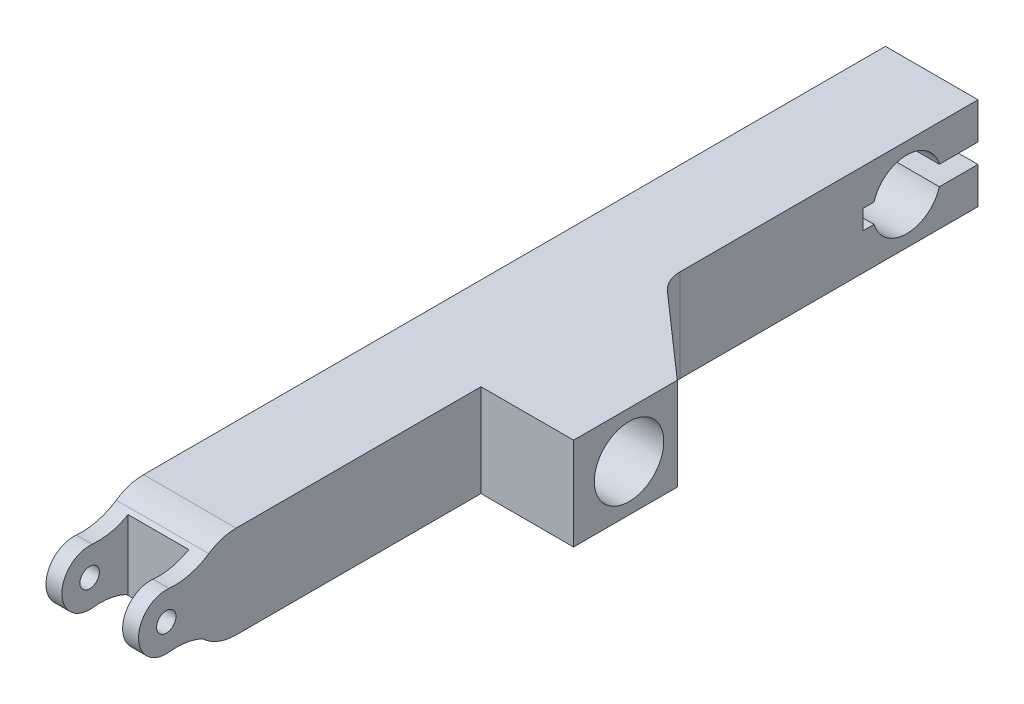
SolidWorks part; units mm, degrees
material "6061-T6 (SS)"
ref_plane "Front Plane" through (0, 0, 0) normal (0, 0, 1) x (1, 0, 0)
ref_plane "Top Plane" through (0, 0, 0) normal (0, 1, 0) x (1, 0, 0)
ref_plane "Right Plane" through (0, 0, 0) normal (1, 0, 0) x (0, 0, -1)
sketch "Sketch1" plane through (0, 0, 0) normal (1, 0, 0) x (0, 0, -1)
  line L0 (0, 0) -> (29.3372, 0) construction
  line L1 (29.3372, -19.05) -> (-175.2557, -19.05)
  line L2 (29.3372, -19.05) -> (29.3372, -4)
  line L3 (29.3372, 19.05) -> (-175.2557, 19.05)
  line L4 (-175.2557, -19.05) -> (-175.2557, 19.05)
  line L5 (-18.025, 0) -> (0, 0) construction
  line L6 (-18.025, 4) -> (-13.4425, 4)
  line L7 (-18.025, 4) -> (-18.025, -4)
  line L8 (-18.025, -4) -> (-13.4425, -4)
  line L10 (29.3372, 4) -> (29.3372, 19.05)
  line L11 (13.4425, 4) -> (29.3372, 4)
  line L12 (13.4425, -4) -> (29.3372, -4)
  line L13 (0, 0) -> (-152.4, 0) construction
  arc A0 (13.4425, 4) -> (-13.4425, 4) centre (0, 0) ccw
  arc A1 (-13.4425, -4) -> (13.4425, -4) centre (0, 0) ccw
  circle A2 centre (-152.4, 0) radius 14.2875
  point P13 (-14.025, 0)
  dimension "D1" = 28.05
  dimension "D6" = 28.575
  dimension "D2" = 8
  dimension "D3" = 4
  dimension "D4" = 38.1
  dimension "D5" = 152.4
extrude "Boss-Extrude1" add sketch "Sketch1" along normal blind 38.1
sketch "Sketch2" plane through (38.1, 0, 0) normal (1, 0, 0) x (0, 0, -1)
  line L0 (-175.2557, -19.05) -> (29.3372, -19.05) construction
  line L1 (-175.2557, 19.05) -> (-99.0557, 19.05)
  line L2 (-175.2557, 19.05) -> (-175.2557, -19.05)
  line L3 (-175.2557, -19.05) -> (-99.0557, -19.05)
  line L4 (-99.0557, 19.05) -> (-99.0557, -19.05)
  circle A0 centre (-152.4, 0) radius 14.2875 construction
  circle A1 centre (-152.4, 0) radius 14.2875
  dimension "D1" = 76.2
extrude "Boss-Extrude2" add sketch "Sketch2" along normal blind 38.1
sketch "Sketch3" plane through (0, 19.05, 0) normal (0, 1, 0) x (1, 0, 0)
  line L0 (38.1, -99.0557) -> (76.2, -132.5624)
  line L1 (76.2, -99.0557) -> (76.2, -175.2557) construction
  line L2 (38.1, -99.0557) -> (94.2773, -84.4492)
  line L3 (94.2773, -84.4492) -> (76.2, -132.5624)
extrude "Cut-Extrude1" cut sketch "Sketch3" against normal blind 38.1
fillet "Fillet1" radius 12.7 1 edges at (38.1, 0, 99.0557)
sketch "Sketch4" plane through (0, 0, 175.2557) normal (0, 0, 1) x (1, 0, 0)
  line L0 (38.1, 19.05) -> (38.1, -19.05)
  line L4 (0, 19.05) -> (0, -19.05)
  line L5 (0, -19.05) -> (76.2, -19.05)
  line L6 (76.2, -19.05) -> (76.2, 19.05)
  line L7 (76.2, 19.05) -> (0, 19.05)
  line L8 (0, 19.05) -> (0, -19.05)
  line L9 (0, -19.05) -> (38.1, -19.05)
  line L11 (38.1, 19.05) -> (0, 19.05)
  dimension "D2" = 38.1
  dimension "D3" = 38.1
  dimension "D1" = 0
extrude "Boss-Extrude3" add sketch "Sketch4" along normal blind 152.4
sketch "Sketch5" plane through (0, 0, 0) normal (-1, 0, 0) x (0, 0, 1)
  line L0 (152.4, 0) -> (304.8, 0) construction
  line L1 (0, 0) -> (152.4, 0) construction
  line L2 (327.6557, -19.05) -> (-29.3372, -19.05) construction
  line L3 (-29.3372, 19.05) -> (327.6557, 19.05) construction
  line L4 (327.6557, -19.05) -> (-29.3372, -19.05) construction
  line L5 (-29.3372, 19.05) -> (327.6557, 19.05) construction
  line L6 (292.4673, 0) -> (304.8, 0) construction
  line L7 (276.062, 19.05) -> (276.062, 26.7418)
  line L8 (276.062, 26.7418) -> (335.0382, 26.7418)
  line L9 (335.0382, 26.7418) -> (335.0382, -31.4269)
  line L10 (335.0382, -31.4269) -> (276.062, -31.4269)
  line L11 (276.062, -31.4269) -> (276.062, -19.05)
  circle A0 centre (152.4, 0) radius 14.2875 construction
  circle A1 centre (152.4, 0) radius 14.2875 construction
  circle A2 centre (304.8, 0) radius 4
  circle A3 centre (304.8, 0) radius 11.43
  arc A4 (287.3047, 15.5909) -> (303.7201, 11.3789) centre (301.3581, 36.267) ccw
  arc A5 (303.4267, -11.3472) -> (289.9026, -13.4874) centre (300.4229, -36.1661) ccw
  arc A6 (287.3047, 15.5909) -> (276.062, 19.05) centre (276.062, -0.95) ccw
  arc A7 (289.9026, -13.4874) -> (276.062, -19.05) centre (276.062, 0.95) cw
  line M15 (-29.3372, -19.05) -> (327.6557, -19.05)
  line M16 (327.6557, -19.05) -> (327.6557, 19.05)
  line M17 (327.6557, 19.05) -> (-29.3372, 19.05)
  dimension "D1" = 8
  dimension "D2" = 22.86
  dimension "D3" = 20
  dimension "D4" = 25
extrude "Cut-Extrude2" cut sketch "Sketch5" against normal blind 152.4 contours L11 L10 L9 L8 L7 M17 M16 M15 | A5 A7 A6 A4 A3 M15 M16 M17 | A2
sketch "Sketch6" plane through (0, -19.05, 0) normal (0, -1, 0) x (1, 0, 0)
  line L0 (19.05, 316.23) -> (19.05, 264.6122) construction
  line L1 (38.1, 316.23) -> (0, 316.23) construction
  line L7 (31.55, 343.4899) -> (6.55, 343.4899)
  line L8 (31.55, 343.4899) -> (31.55, 288.9701)
  line L9 (31.55, 288.9701) -> (6.55, 288.9701)
  line L10 (6.55, 343.4899) -> (6.55, 288.9701)
  line L11 (31.55, 343.4899) -> (6.55, 288.9701) construction
  line L12 (31.55, 288.9701) -> (6.55, 343.4899) construction
  dimension "D1" = 25
extrude "Cut-Extrude3" cut sketch "Sketch6" against normal blind 152.4
